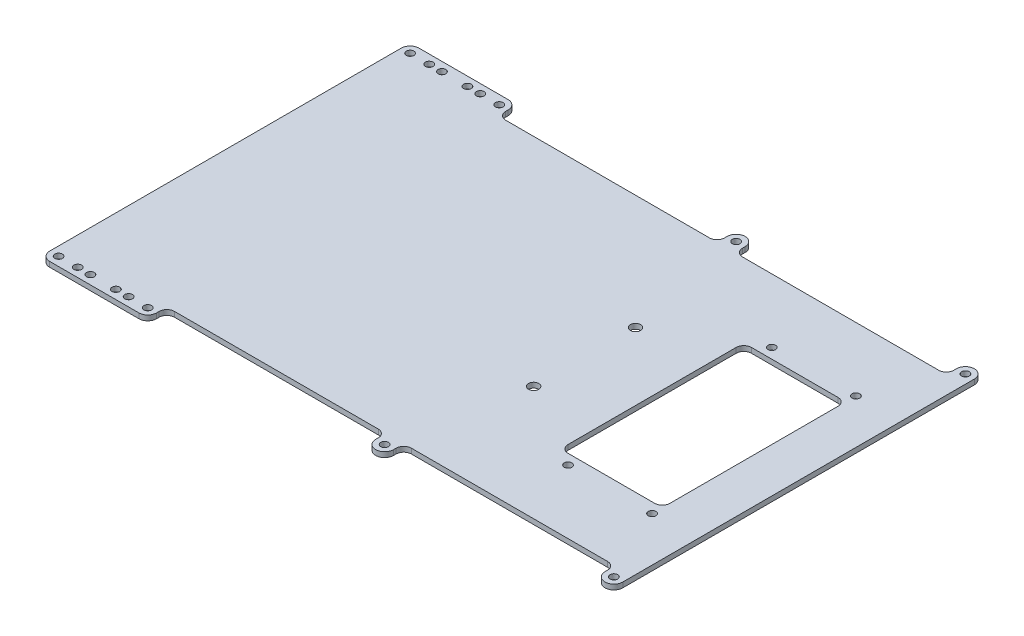
SolidWorks part; units mm, degrees
ref_plane "Front Plane" through (0, 0, 0) normal (0, 0, 1) x (1, 0, 0)
ref_plane "Top Plane" through (0, 0, 0) normal (0, 1, 0) x (1, 0, 0)
ref_plane "Right Plane" through (0, 0, 0) normal (1, 0, 0) x (0, 0, -1)
sketch "Sketch1" plane through (0, 0, 0) normal (0, 1, 0) x (1, 0, 0)
  line L0 (0, 100) -> (0, -100) construction
  line L1 (-143.7838, 0) -> (115.027, 0) construction
  line L2 (-120, 69) -> (0, 69) construction
  line L16 (45, 20) -> (45, -20) construction
  line L34 (-96, 72.5) -> (129, 72.5)
  line L35 (-96, -72.5) -> (129, -72.5)
  line L37 (129, 72.5) -> (129, -72.5)
  line L52 (-96, 72.5) -> (-96, -72.5)
  line L53 (-100, -69) -> (-50, -69) construction
  line L54 (95, 40) -> (95, -40) construction
  line L60 (78.5, 40) -> (111.5, 40) construction
  line L61 (78.5, 40) -> (78.5, 10) construction
  line L62 (78.5, -40) -> (111.5, -40) construction
  line L63 (111.5, 40) -> (111.5, -40) construction
  line L65 (111.5, 36) -> (111.5, -36)
  line L70 (78.5, 10) -> (78.5, -40) construction
  line L79 (111.5, 36) -> (71.5, 36)
  line L80 (71.5, 36) -> (71.5, -36)
  line L81 (71.5, -36) -> (111.5, -36)
  circle A0 centre (-85, 69) radius 1.5
  circle A1 centre (-75, 69) radius 1.5 construction
  circle A2 centre (-65, 69) radius 1.5
  circle A3 centre (-85, -69) radius 1.5
  circle A4 centre (-75, -69) radius 1.5 construction
  circle A5 centre (-65, -69) radius 1.5
  circle A6 centre (45, 20) radius 2
  circle A7 centre (45, -20) radius 2
  circle A34 centre (-80, 69) radius 1.5
  circle A35 centre (-70, 69) radius 1.5
  circle A36 centre (-80, -69) radius 1.5
  circle A37 centre (-70, -69) radius 1.5
  circle A38 centre (78.5, -40) radius 1.5
  circle A39 centre (111.5, -40) radius 1.5
  circle A40 centre (111.5, 40) radius 1.5
  circle A41 centre (78.5, 40) radius 1.5
  circle A42 centre (-92.5, -69) radius 1.5
  circle A43 centre (-57.5, -69) radius 1.5
  circle A44 centre (-92.5, 69) radius 1.5
  circle A45 centre (-57.5, 69) radius 1.5
  point P5 (-96, 0)
  point P14 (129, 0)
  point P36 (45, 0)
  point P45 (95, 40)
  point P46 (111.5, 0)
  point P60 (95, -40)
  point P61 (0, 0)
  point P62 (-75, -69)
  dimension "D4" = 3
  dimension "D5" = 3
  dimension "D6" = 3
  dimension "D7" = 10
  dimension "D8" = 10
  dimension "D9" = 3.5
  dimension "D15" = 4
  dimension "D16" = 4
  dimension "D21" = 80
  dimension "D22" = 3
  dimension "D23" = 3
  dimension "D24" = 5
  dimension "D28" = 5
  dimension "D29" = 3
  dimension "D30" = 3
  dimension "D31" = 170
  dimension "D35" = 72
  dimension "D36" = 120
  dimension "D37" = 200
  dimension "D38" = 50
  dimension "D42" = 3
  dimension "D43" = 35
  dimension "D47" = 3
  dimension "D19" = 33
  dimension "D17" = 3
  dimension "D18" = 3
  dimension "D20" = 5
  dimension "D25" = 3
  dimension "D26" = 3
  dimension "D27" = 5
  dimension "D39" = 35
  dimension "D40" = 17.5
  dimension "D41" = 3
  dimension "D45" = 17.5
  dimension "D46" = 3
  dimension "D10" = 75
  dimension "D11" = 96
  dimension "D12" = 129
  dimension "D13" = 120
  dimension "D14" = 40
  dimension "D32" = 40
  dimension "D33" = 36
  dimension "D44" = 145
extrude "Boss-Extrude1" add sketch "Sketch1" along normal blind 2
sketch "Sketch3" plane through (0, 2, 0) normal (0, 1, 0) x (1, 0, 0)
  line L0 (-54, 72.5) -> (-54, 65)
  line L1 (129, 72.5) -> (-96, 72.5) construction
  line L3 (-96, 72.5) -> (-96, -72.5) construction
  line L4 (32, 65) -> (39, 65)
  line L5 (129, -72.5) -> (129, 72.5) construction
  line L6 (-138.3638, 0) -> (163.9786, 0) construction
  line L7 (129, 65) -> (129, 69)
  line L9 (32, 65) -> (32, 69)
  line L10 (39, 65) -> (39, 69)
  line L12 (122, 65) -> (122, 69)
  line L13 (122, 65) -> (129, 65)
  line L18 (129, 72.5) -> (-54, 72.5)
  line L20 (129, -65) -> (129, -72.5)
  line L21 (-54, 65) -> (32, 65)
  line L22 (39, 65) -> (122, 65)
  line L23 (129, 65) -> (129, 72.5)
  line L24 (39, -65) -> (122, -65)
  line L25 (-54, -65) -> (32, -65)
  line L26 (129, -72.5) -> (-54, -72.5)
  line L27 (122, -65) -> (129, -65)
  line L28 (122, -65) -> (122, -69)
  line L29 (39, -65) -> (39, -69)
  line L30 (32, -65) -> (32, -69)
  line L31 (129, -65) -> (129, -69)
  line L32 (32, -65) -> (39, -65)
  line L33 (-54, -72.5) -> (-54, -65)
  arc A0 (39, 69) -> (32, 69) centre (35.5, 69) ccw
  circle A1 centre (35.5, 69) radius 1.5
  arc A2 (129, 69) -> (122, 69) centre (125.5, 69) ccw
  circle A3 centre (125.5, 69) radius 1.5
  circle A8 centre (125.5, -69) radius 1.5
  arc A9 (129, -69) -> (122, -69) centre (125.5, -69) cw
  circle A10 centre (35.5, -69) radius 1.5
  arc A11 (39, -69) -> (32, -69) centre (35.5, -69) cw
  point P22 (32, 67)
  line M19 (-96, -72.5) -> (129, -72.5)
  line M20 (129, -72.5) -> (129, 72.5)
  line M21 (129, 72.5) -> (-96, 72.5)
  dimension "D6" = 7
  dimension "D7" = 3
  dimension "D9" = 7
  dimension "D10" = 3
  dimension "D3" = 90
  dimension "D1" = 42
  dimension "D2" = 7.5
  dimension "D5" = 7
  dimension "D8" = 7
extrude "Cut-Extrude1" cut sketch "Sketch3" against normal blind 10 contours A11 L30 L25 L33 M19 | L29 A11 L26 A9 L28 L24 | A0 L18 L0 L21 L9 | A2 L18 A0 L10 L22 L12 | A2 M20 M21 | A3 | A1 | A10 | A9 L26 M20 | A8
fillet "Fillet3" radius 3 4 edges at (111.5, 1, 36) (71.5, 1, 36) (111.5, 1, -36) (71.5, 1, -36)
fillet "Fillet4" radius 3 8 edges at (122, 1, 65) (39, 1, 65) (32, 1, 65) (-54, 1, 65) (122, 1, -65) (39, 1, -65) (32, 1, -65) (-54, 1, -65)
fillet "Fillet5" radius 3.5 4 edges at (-54, 1, 72.5) (-96, 1, 72.5) (-54, 1, -72.5) (-96, 1, -72.5)
